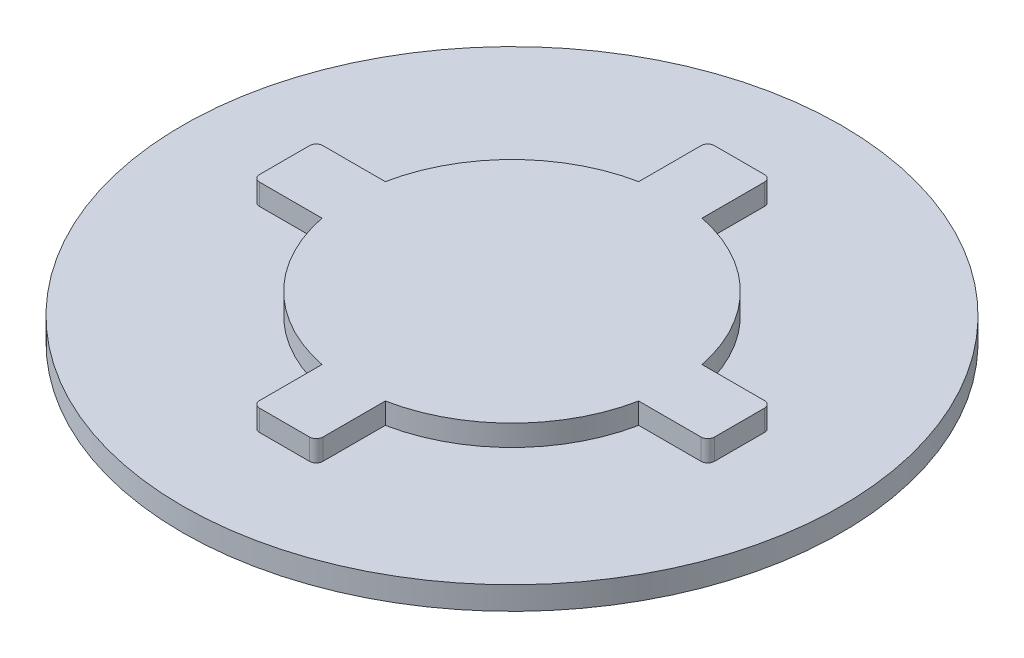
SolidWorks part; units mm, degrees
ref_plane "Alzado" through (0, 0, 0) normal (0, 0, 1) x (1, 0, 0)
ref_plane "Planta" through (0, 0, 0) normal (0, 1, 0) x (1, 0, 0)
ref_plane "Vista lateral" through (0, 0, 0) normal (1, 0, 0) x (0, 0, -1)
sketch "Croquis5" plane through (0, 0, 0) normal (0, 1, 0) x (1, 0, 0)
  circle A0 centre (0, 0) radius 24.5
  dimension "D1" = 49
extrude "Saliente-Extruir3" add sketch "Croquis5" along normal blind 3.2
sketch "Croquis6" plane through (0, 0, 0) normal (0, -1, 0) x (1, 0, 0)
  line L1 (33.5, 4.8) -> (-33.5, 4.8)
  line L2 (34.5, 3.8) -> (34.5, -3.8)
  line L3 (33.5, -4.8) -> (-33.5, -4.8)
  line L4 (-34.5, 3.8) -> (-34.5, -3.8)
  line L5 (34.5, 4.8) -> (-34.5, -4.8) construction
  line L6 (34.5, -4.8) -> (-34.5, 4.8) construction
  line L10 (3.8, -34.5) -> (-3.8, -34.5)
  line L11 (4.8, -33.5) -> (4.8, 33.5)
  line L12 (3.8, 34.5) -> (-3.8, 34.5)
  line L13 (-4.8, -33.5) -> (-4.8, 33.5)
  arc A0 (-3.8, -34.5) -> (-4.8, -33.5) centre (-3.8, -33.5) cw
  arc A1 (33.5, 4.8) -> (34.5, 3.8) centre (33.5, 3.8) cw
  arc A2 (34.5, -3.8) -> (33.5, -4.8) centre (33.5, -3.8) cw
  arc A3 (-33.5, -4.8) -> (-34.5, -3.8) centre (-33.5, -3.8) cw
  arc A4 (-33.5, 4.8) -> (-34.5, 3.8) centre (-33.5, 3.8) ccw
  arc A5 (4.8, -33.5) -> (3.8, -34.5) centre (3.8, -33.5) cw
  arc A6 (4.8, 33.5) -> (3.8, 34.5) centre (3.8, 33.5) ccw
  arc A7 (-4.8, 33.5) -> (-3.8, 34.5) centre (-3.8, 33.5) cw
  point P0 (0, 0)
  point P13 (0, 0)
  point P34 (0, 0)
  dimension "D4" = 1
  dimension "D1" = 69
  dimension "D2" = 9.6
extrude "Saliente-Extruir4" add sketch "Croquis6" against normal blind 3.2
sketch "Croquis7" plane through (0, 0, 0) normal (0, -1, 0) x (1, 0, 0)
  circle A0 centre (0, 0) radius 50
  dimension "D1" = 100
extrude "Saliente-Extruir5" add sketch "Croquis7" along normal blind 3.5
sketch "Croquis8" plane through (0, -3.5, 0) normal (0, -1, 0) x (1, 0, 0)
  line L0 (2.5, -25) -> (-2.5, -25)
  line L1 (25, 2.5) -> (-25, 2.5)
  line L2 (25, 2.5) -> (25, -2.5)
  line L3 (25, -2.5) -> (-25, -2.5)
  line L4 (-25, 2.5) -> (-25, -2.5)
  line L5 (25, 2.5) -> (-25, -2.5) construction
  line L6 (25, -2.5) -> (-25, 2.5) construction
  line L7 (2.5, -25) -> (2.5, 25)
  line L8 (2.5, 25) -> (-2.5, 25)
  line L9 (-2.5, -25) -> (-2.5, 25)
  circle A0 centre (0, 0) radius 15
  circle A1 centre (0, 0) radius 20
  point P0 (0, 0)
  point P13 (0, 0)
  dimension "D3" = 30
  dimension "D4" = 40
  dimension "D1" = 50
  dimension "D2" = 5
extrude "Cortar-Extruir3" cut sketch "Croquis8" against normal blind 2 contours A1 L9 L0 L7 | L9 A1 L7 A0 | L9 A0 L7 L3 | L9 L3 L7 L1 | L7 A0 L9 L1 | L7 A1 L9 A0 | A1 L7 L8 L9 | L3 A0 L1 L7 | L3 A1 L1 A0 | A1 L3 L2 L1 | L1 A0 L3 L9 | L1 A1 L3 A0 | A1 L1 L4 L3 | L9 A1 L1 A0 | L1 A1 L7 A0 | L7 A1 L3 A0 | L3 A1 L9 A0
sketch "Croquis9" plane through (0, -1.5, 0) normal (0, -1, 0) x (1, 0, 0)
  line L0 (-25, 0) -> (25, 0) construction
  line L1 (-25, 2.5) -> (-25, -2.5) construction
  line L2 (25, 2.5) -> (25, -2.5) construction
  line L3 (0, -25) -> (0, 25) construction
  line L4 (2.5, -25) -> (-2.5, -25) construction
  line L5 (2.5, 25) -> (-2.5, 25) construction
  circle A0 centre (0, 0) radius 22.5 construction
  circle A1 centre (0, 0) radius 3.5355
  dimension "D1" = 45
extrude "Cortar-Extruir4" cut sketch "Croquis9" against normal blind 2.5
sketch "Croquis10" plane through (0, -1.5, 0) normal (0, -1, 0) x (1, 0, 0)
  line L0 (-25, 0) -> (25, 0) construction
  line L1 (-25, 2.5) -> (-25, -2.5) construction
  line L2 (25, 2.5) -> (25, -2.5) construction
  line L3 (0, 25) -> (0, -25) construction
  line L4 (2.5, 25) -> (-2.5, 25) construction
  line L5 (2.5, -25) -> (-2.5, -25) construction
  circle A0 centre (0, 0) radius 22.5 construction
  circle A1 centre (-22.5, 0) radius 0.5
  circle A2 centre (0, 22.5) radius 0.5
  circle A3 centre (22.5, 0) radius 0.5
  circle A4 centre (0, -22.5) radius 0.5
  point P26 (0, 0)
  dimension "D1" = 45
  dimension "D2" = 1
  dimension "D3" = 4
extrude "Cortar-Extruir5" [suppressed] cut sketch "Croquis10" against normal blind 2
